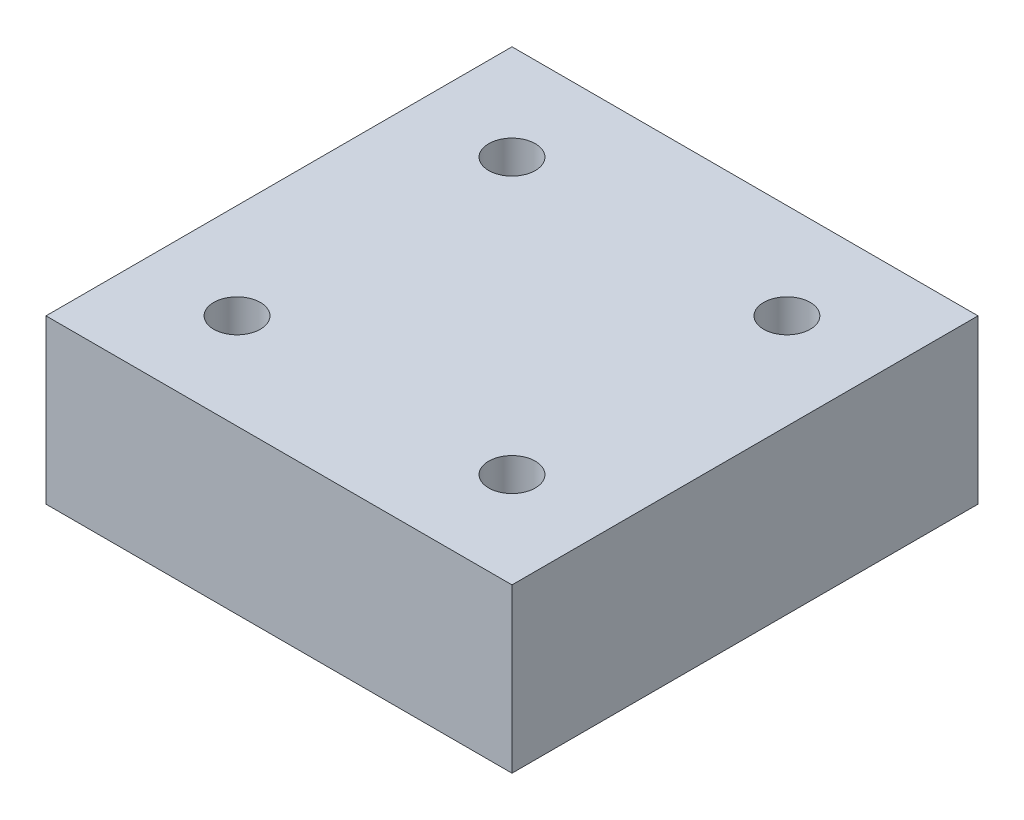
SolidWorks part; units mm, degrees
ref_plane "Front Plane" through (0, 0, 0) normal (0, 0, 1) x (1, 0, 0)
ref_plane "Top Plane" through (0, 0, 0) normal (0, 1, 0) x (1, 0, 0)
ref_plane "Right Plane" through (0, 0, 0) normal (1, 0, 0) x (0, 0, -1)
sketch "Sketch1" plane through (0, 0, 0) normal (0, 1, 0) x (1, 0, 0)
  line L1 (-25.4, -25.4) -> (25.4, -25.4)
  line L2 (-25.4, -25.4) -> (-25.4, 25.4)
  line L3 (-25.4, 25.4) -> (25.4, 25.4)
  line L4 (25.4, -25.4) -> (25.4, 25.4)
  line L5 (-25.4, -25.4) -> (25.4, 25.4) construction
  line L6 (-25.4, 25.4) -> (25.4, -25.4) construction
  point P0 (0, 0)
  dimension "D1" = 50.8
  dimension "D2" = 50.8
extrude "Boss-Extrude1" add sketch "Sketch1" along normal blind 17.78
sketch "Sketch2" plane through (0, 17.78, 0) normal (0, 1, 0) x (1, 0, 0)
  line L1 (-14.986, -14.986) -> (14.986, -14.986) construction
  line L2 (-14.986, -14.986) -> (-14.986, 14.986) construction
  line L3 (-14.986, 14.986) -> (14.986, 14.986) construction
  line L4 (14.986, -14.986) -> (14.986, 14.986) construction
  line L5 (-14.986, -14.986) -> (14.986, 14.986) construction
  line L6 (-14.986, 14.986) -> (14.986, -14.986) construction
  circle A0 centre (-14.986, 14.986) radius 2.54
  circle A1 centre (14.986, 14.986) radius 2.54
  circle A2 centre (14.986, -14.986) radius 2.54
  circle A3 centre (-14.986, -14.986) radius 2.54
  point P0 (0, 0)
  dimension "D3" = 5.08
  dimension "D4" = 5.08
  dimension "D5" = 5.08
  dimension "D6" = 5.08
  dimension "D1" = 29.972
  dimension "D2" = 29.972
extrude "Cut-Extrude1" cut sketch "Sketch2" against normal through all
